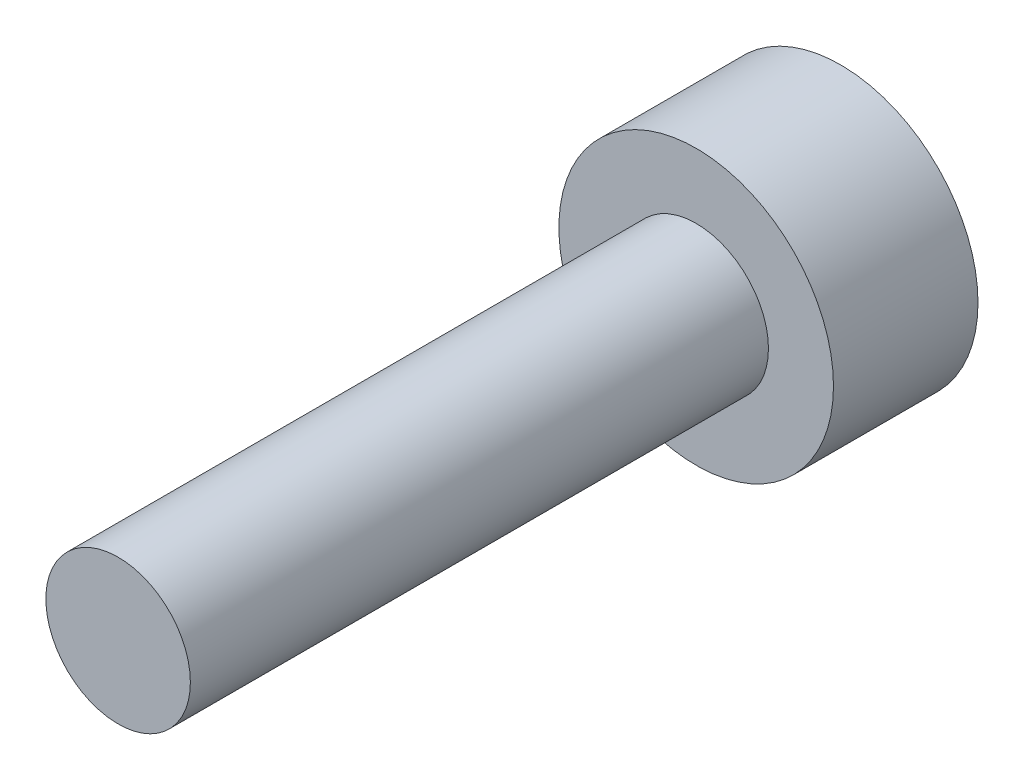
SolidWorks part; units mm, degrees
material "AISI 4340 Steel, normalized"
ref_plane "Front Plane" through (0, 0, 0) normal (0, 0, 1) x (1, 0, 0)
ref_plane "Top Plane" through (0, 0, 0) normal (0, 1, 0) x (1, 0, 0)
ref_plane "Right Plane" through (0, 0, 0) normal (1, 0, 0) x (0, 0, -1)
sketch "Sketch1" plane through (0, 0, 0) normal (0, 0, 1) x (1, 0, 0)
  circle A0 centre (0, 0) radius 1.9
extrude "Head_Envelope" add sketch "Sketch1" along normal blind 2 from offset 2
sketch "Sketch2" plane through (0, 0, 0) normal (0, 0, 1) x (1, 0, 0)
  circle A0 centre (0, 0) radius 1
extrude "Thread_Major_Envelope" add sketch "Sketch2" along normal blind 8
